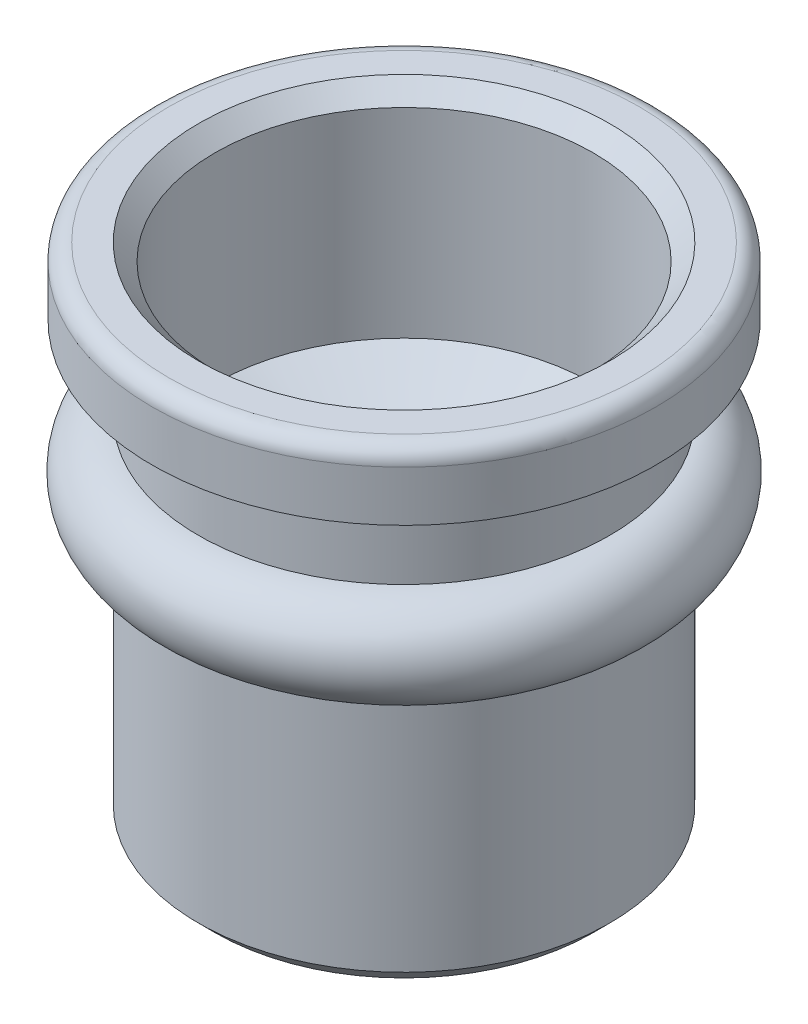
SolidWorks part; units mm, degrees
ref_plane "Спереди" through (0, 0, 0) normal (0, 0, 1) x (1, 0, 0)
ref_plane "Сверху" through (0, 0, 0) normal (0, 1, 0) x (1, 0, 0)
ref_plane "Справа" through (0, 0, 0) normal (1, 0, 0) x (0, 0, -1)
sketch "Эскиз1" plane through (0, 0, 0) normal (0, 0, 1) x (1, 0, 0)
  line L0 (0, 0) -> (0, 5.6174) construction
  line L1 (0, 0) -> (2.45, 0)
  line L2 (2.45, 0) -> (2.45, 5.2)
  line L3 (2.45, 5.2) -> (3, 5.2)
  line L4 (3, 5.2) -> (3, 6)
  line L5 (3, 6) -> (0, 6)
  line L6 (0, 6) -> (0, 0)
  dimension "D1" = 0.8
  dimension "D2" = 6
  dimension "D3" = 2.45
  dimension "D4" = 3
revolve "Повернуть1" add sketch "Эскиз1" angle 360 about L0
fillet "Скругление2" radius 0.2 1 edges at (0, 6, -3)
hole_wizard "Отверстие обработанное метчиком M31" positions "Эскиз5" profile "Эскиз6" tap size "M3" standard "DIN"
sketch "Эскиз5" plane through (0, 0, 0) normal (0, -1, 0) x (-1, 0, 0)
  point P0 (0, 0)
sketch "Эскиз6" plane through (0, 0, 0) normal (1, 0, 0) x (0, 0, -1)
  line L0 (0, 0) -> (0, 4.7511)
  line L1 (0, 4.7511) -> (1.25, 4)
  line L2 (1.25, 4) -> (1.25, 0)
  line L5 (1.25, 0) -> (0, 0)
  line L10 (0, 4.7511) -> (-1.25, 4) construction
  line L11 (0, -6.35) -> (0, 107.95) construction
  dimension "Диаметр сверла" = 2.5
  dimension "Глубина сверла" = 4
  dimension "Угол заточки сверла" = 118
cosmetic thread "Отверстие резьбы1" parameters "D1"=4, "D2"=3
chamfer "Фаска2" distance 0.15 angle 45 1 edges at (0, 0, -1.25)
sketch "Эскиз8" plane through (0, 0, 0) normal (0, 0, 1) x (1, 0, 0)
  line L0 (0, 6) -> (0, 4.0112) construction
  line L1 (2.8, 6) -> (-2.8, 6) construction
  line L2 (2.25, 6) -> (2.25, 3.4197)
  line L3 (2.25, 3.4197) -> (1.35, 3)
  line L4 (1.35, 3) -> (0, 3)
  line L5 (0, 3) -> (0, 6)
  line L6 (0, 6) -> (2.25, 6)
  dimension "D1" = 4.5
  dimension "D2" = 65
  dimension "D3" = 3
  dimension "D4" = 1.35
revolve "Вырез-Повернуть1" cut sketch "Эскиз8" angle 360 about L0
sketch "Эскиз9" plane through (0, 0, 0) normal (0, 0, 1) x (1, 0, 0)
  line L6 (-2.45, 5.2) -> (-2.45, 0) construction
  line L13 (0, 0) -> (0, 6) construction
  line L15 (-2.45, 4.2) -> (-2.45, 3.08)
  line L16 (2.25, 6) -> (-2.25, 6) construction
  line L17 (0, 6) -> (0, 0) construction
  line L18 (0, 0) -> (0, 6) construction
  arc A0 (-2.45, 4.2) -> (-2.45, 3.08) centre (-2.45, 3.64) ccw
revolve "Повернуть3" add sketch "Эскиз9" angle 360 about L13
chamfer "Фаска3" distance 0.2 angle 45 1 edges at (0, 0, -2.45)
chamfer "Фаска4" [suppressed] distance 0.2 angle 45
chamfer "Фаска5" [suppressed] distance 0.2 angle 45
chamfer "Фаска6" distance 0.2 angle 45 1 edges at (0, 6, 2.25)
